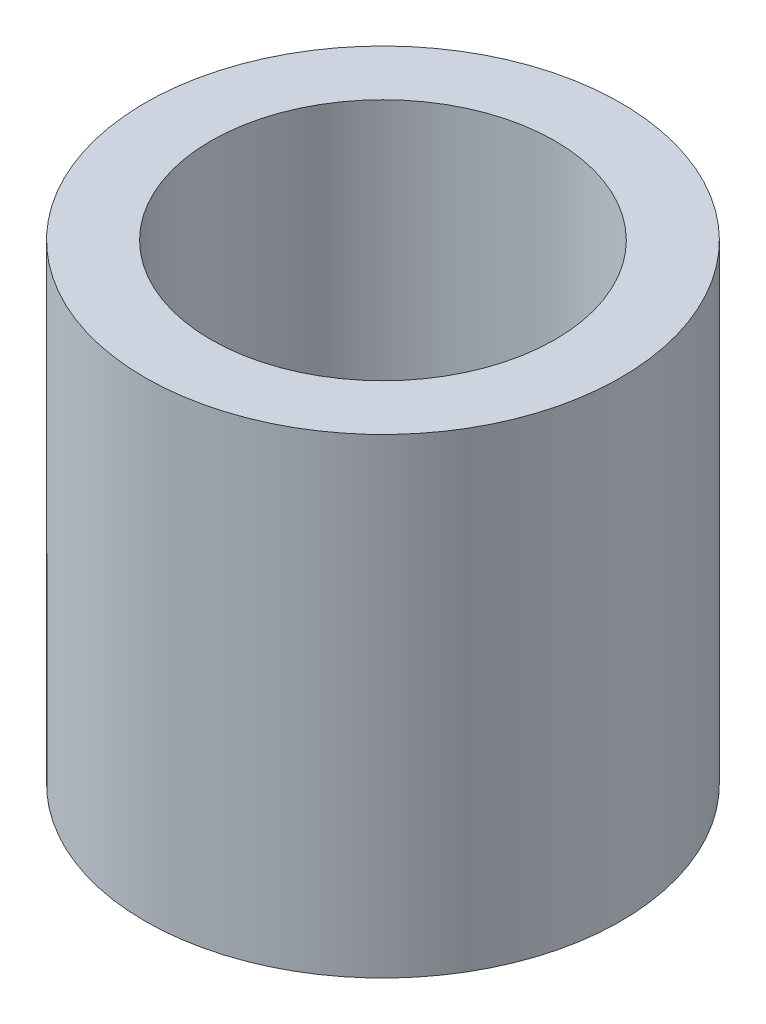
SolidWorks part; units mm, degrees
material "ABS"
ref_plane "Plan de face" through (0, 0, 0) normal (0, 0, 1) x (1, 0, 0)
ref_plane "Plan de dessus" through (0, 0, 0) normal (0, 1, 0) x (1, 0, 0)
ref_plane "Plan de droite" through (0, 0, 0) normal (1, 0, 0) x (0, 0, -1)
sketch "Esquisse2" plane through (0, 0, 0) normal (0, 1, 0) x (1, 0, 0)
  circle A0 centre (0, 0) radius 1.7
  circle A1 centre (0, 0) radius 2.35
  dimension "D1" = 3.4
  dimension "D2" = 4.7
extrude "Boss.-Extru.1" add sketch "Esquisse2" along normal blind 4.65
equation "\"entretoiseBearing\"= 1.5mm"
equation "\"length_tibia\"= 206mm"
equation "\"length_femur\"= 117mm"
equation "\"length_coxa\"= 27mm"
equation "\"height\"= 40mm"
equation "\"width\"= 100mm"
equation "\"lever\"= 40mm"
equation "\"errorFlat\"= 0.20mm"
equation "\"errorFlat_tight\"= 0.15mm"
equation "\"errorCircle\"= 0.40mm"
equation "\"errorCircle_tight\" = 0.30mm"
equation "\"cuticule\"=1.5mm"
equation "\"cuticule_attach_w\"=10mm"
equation "\"cuticule_attach_h\"=2.5mm"
equation "\"depthMagnet\"= 1mm"
equation "\"insert_d\" = 3.2mm"
equation "\"insert_l\" = 5mm"
equation "\"D1@Esquisse2\"= 3 + \"errorCircle\""
equation "\"D2@Esquisse2\"= 5 - \"errorCircle_tight\""
equation "\"D1@Boss.-Extru.1\"= 3.5+1.30 - \"errorFlat_tight\""
